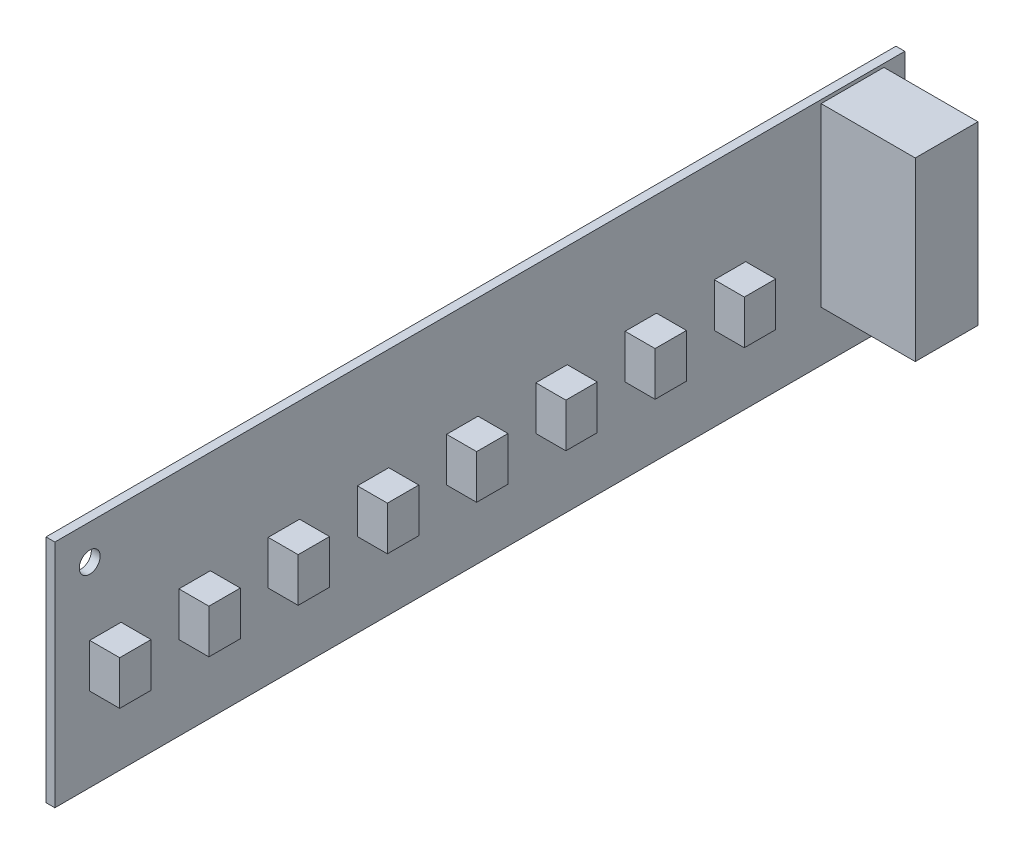
SolidWorks part; units mm, degrees
ref_plane "Front Plane" through (0, 0, 0) normal (0, 0, 1) x (1, 0, 0)
ref_plane "Top Plane" through (0, 0, 0) normal (0, 1, 0) x (1, 0, 0)
ref_plane "Right Plane" through (0, 0, 0) normal (1, 0, 0) x (0, 0, -1)
sketch "Sketch1" plane through (0, 0, 0) normal (1, 0, 0) x (0, 0, -1)
  line L1 (0, 0) -> (121.92, 0)
  line L2 (0, 0) -> (0, 33.02)
  line L3 (0, 33.02) -> (121.92, 33.02)
  line L4 (121.92, 0) -> (121.92, 33.02)
  circle A0 centre (5, 28.02) radius 1.5
  dimension "D5" = 3
  dimension "D1" = 33.02
  dimension "D2" = 121.92
  dimension "D3" = 5
  dimension "D4" = 5
extrude "Boss-Extrude1" add sketch "Sketch1" along normal blind 1.27
sketch "Sketch2" plane through (1.27, 0, 0) normal (1, 0, 0) x (0, 0, -1)
  line L0 (121.92, 0) -> (121.92, 33.02) construction
  line L1 (118.92, 32.52) -> (109.92, 32.52)
  line L2 (118.92, 32.52) -> (118.92, 7.22)
  line L3 (118.92, 7.22) -> (109.92, 7.22)
  line L4 (109.92, 32.52) -> (109.92, 7.22)
  line L5 (121.92, 33.02) -> (0, 33.02) construction
  dimension "D1" = 25.3
  dimension "D2" = 9
  dimension "D3" = 3
  dimension "D4" = 0.5
extrude "Boss-Extrude2" add sketch "Sketch2" along normal blind 13.5
sketch "Sketch3" plane through (1.27, 0, 0) normal (1, 0, 0) x (0, 0, -1)
  line L0 (0, 33.02) -> (0, 0) construction
  line L1 (5, 18.3) -> (9.5, 18.3)
  line L2 (5, 18.3) -> (5, 12)
  line L3 (5, 12) -> (9.5, 12)
  line L4 (9.5, 18.3) -> (9.5, 12)
  line L5 (0, 0) -> (121.92, 0) construction
  line L6 (17.8, 18.3) -> (22.3, 18.3)
  line L7 (17.8, 18.3) -> (17.8, 12)
  line L8 (17.8, 12) -> (22.3, 12)
  line L9 (22.3, 18.3) -> (22.3, 12)
  line L10 (30.6, 18.3) -> (35.1, 18.3)
  line L11 (30.6, 18.3) -> (30.6, 12)
  line L12 (30.6, 12) -> (35.1, 12)
  line L13 (35.1, 18.3) -> (35.1, 12)
  line L14 (43.4, 18.3) -> (47.9, 18.3)
  line L15 (43.4, 18.3) -> (43.4, 12)
  line L16 (43.4, 12) -> (47.9, 12)
  line L17 (47.9, 18.3) -> (47.9, 12)
  line L18 (56.2, 18.3) -> (60.7, 18.3)
  line L19 (56.2, 18.3) -> (56.2, 12)
  line L20 (56.2, 12) -> (60.7, 12)
  line L21 (60.7, 18.3) -> (60.7, 12)
  line L22 (69, 18.3) -> (73.5, 18.3)
  line L23 (69, 18.3) -> (69, 12)
  line L24 (69, 12) -> (73.5, 12)
  line L25 (73.5, 18.3) -> (73.5, 12)
  line L26 (81.8, 18.3) -> (86.3, 18.3)
  line L27 (81.8, 18.3) -> (81.8, 12)
  line L28 (81.8, 12) -> (86.3, 12)
  line L29 (86.3, 18.3) -> (86.3, 12)
  line L30 (94.6, 18.3) -> (99.1, 18.3)
  line L31 (94.6, 18.3) -> (94.6, 12)
  line L32 (94.6, 12) -> (99.1, 12)
  line L33 (99.1, 18.3) -> (99.1, 12)
  dimension "D1" = 6.3
  dimension "D2" = 4.5
  dimension "D3" = 5
  dimension "D4" = 12
  dimension "D5" = 8
extrude "Boss-Extrude3" add sketch "Sketch3" along normal blind 4.3
